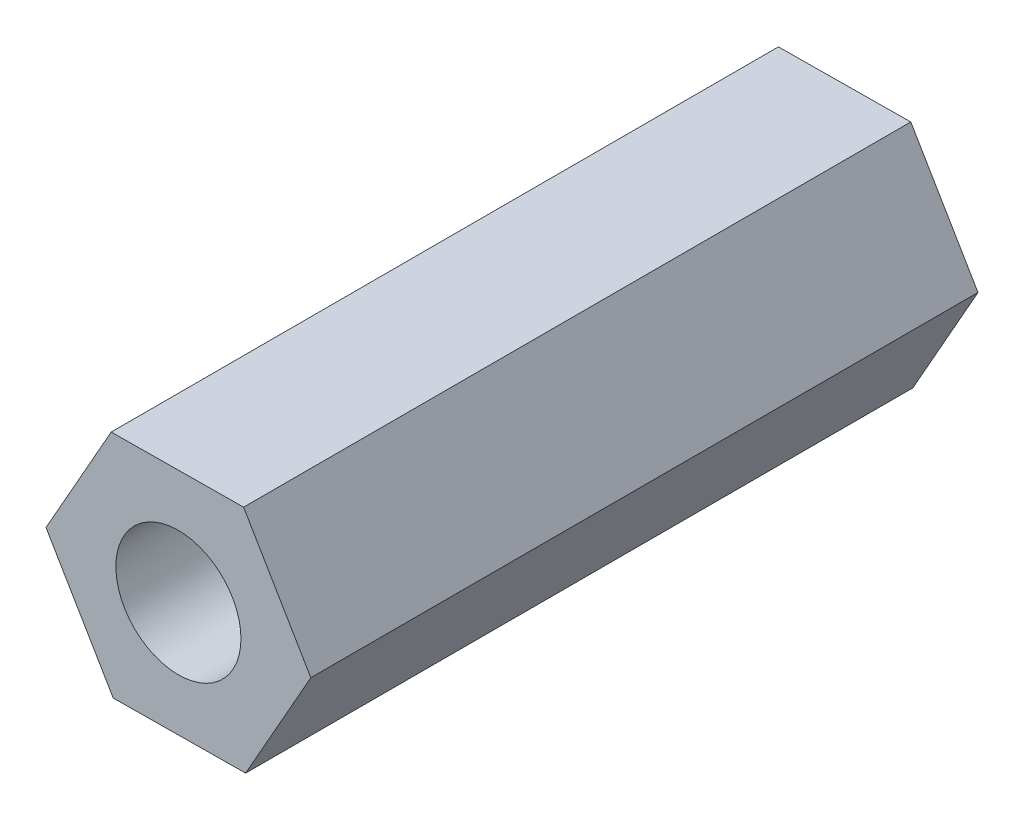
SolidWorks part; units mm, degrees
ref_plane "前视基准面" through (0, 0, 0) normal (0, 0, 1) x (1, 0, 0)
ref_plane "上视基准面" through (0, 0, 0) normal (0, 1, 0) x (1, 0, 0)
ref_plane "右视基准面" through (0, 0, 0) normal (1, 0, 0) x (0, 0, -1)
sketch "草图1" plane through (0, 0, 0) normal (0, 0, 1) x (1, 0, 0)
  line L1 (1.6119, -2.7359) -> (3.1753, 0.028)
  line L2 (3.1753, 0.028) -> (1.5634, 2.7639)
  line L3 (1.5634, 2.7639) -> (-1.6119, 2.7359)
  line L4 (-1.6119, 2.7359) -> (-3.1753, -0.028)
  line L5 (-3.1753, -0.028) -> (-1.5634, -2.7639)
  line L6 (-1.5634, -2.7639) -> (1.6119, -2.7359)
  circle A0 centre (0, 0) radius 2.75 construction
  circle A1 centre (0, 0) radius 1.5
extrude "凸台-拉伸1" add sketch "草图1" along normal blind 16
